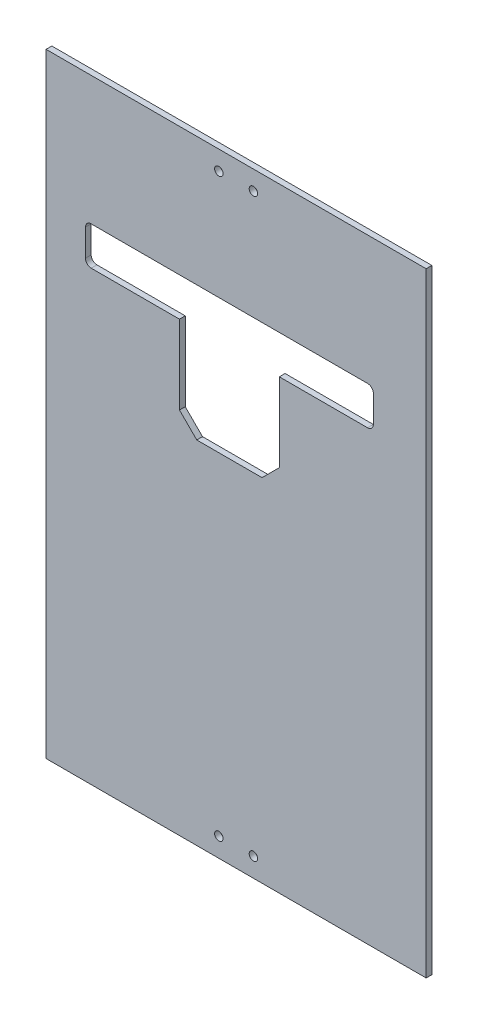
SolidWorks part; units mm, degrees
ref_plane "Plan de face" through (0, 0, 0) normal (0, 0, 1) x (1, 0, 0)
ref_plane "Plan de dessus" through (0, 0, 0) normal (0, 1, 0) x (1, 0, 0)
ref_plane "Plan de droite" through (0, 0, 0) normal (1, 0, 0) x (0, 0, -1)
sketch "Esquisse1" plane through (0, 0, 0) normal (0, 0, 1) x (1, 0, 0)
  line L0 (0, 0) -> (99, 0) construction
  line L1 (0, 0) -> (-99, 0) construction
  line L2 (-99, 0) -> (-99, 165) construction
  line L3 (-99, 165) -> (99, 165)
  line L4 (99, 165) -> (99, -155)
  line L5 (99, -155) -> (-99, -155)
  line L7 (-99, 165) -> (-99, -155)
  dimension "D1" = 165
  dimension "D2" = 99
  dimension "D4" = 320
  dimension "D5" = 320
extrude "Boss.-Extru.1" add sketch "Esquisse1" along normal blind 3
sketch "Esquisse2" plane through (0, 0, 3) normal (0, 0, 1) x (1, 0, 0)
  line L0 (0, -155) -> (0, -145) construction
  line L1 (-99, -155) -> (99, -155) construction
  line L2 (0, -145) -> (9, -145) construction
  line L3 (0, -145) -> (-9, -145) construction
  line L4 (0, 165) -> (0, 155) construction
  line L5 (99, 165) -> (-99, 165) construction
  line L6 (0, 155) -> (9, 155) construction
  line L7 (0, 155) -> (-9, 155) construction
  circle A0 centre (9, -145) radius 2.2
  circle A1 centre (-9, -145) radius 2.2
  circle A2 centre (-9, 155) radius 2.2
  circle A3 centre (9, 155) radius 2.2
  dimension "D1" = 10
  dimension "D2" = 18
  dimension "D3" = 9
  dimension "D4" = 10
  dimension "D5" = 9
  dimension "D6" = 9
extrude "Enlèv. mat.-Extru.1" cut sketch "Esquisse2" against normal up to next
sketch "Esquisse3" plane through (0, 0, 3) normal (0, 0, 1) x (1, 0, 0)
  line L0 (-99, 165) -> (-99, 89)
  line L1 (-99, 165) -> (-99, -155) construction
  line L2 (-99, 89) -> (99, 89)
  line L3 (99, -155) -> (99, 165) construction
  line L4 (99, 89) -> (99, 165)
  line L5 (99, 165) -> (-99, 165)
sketch "Esquisse5" plane through (0, 0, 3) normal (0, 0, 1) x (1, 0, 0)
  line L0 (0, 165) -> (0, 78) construction
  line L1 (99, 165) -> (-99, 165) construction
  line L2 (0, 78) -> (-58.5, 78) construction
  line L3 (-58.5, 78) -> (-78.5, 78)
  line L4 (-78.5, 78) -> (-78.5, 98)
  line L5 (-78.5, 98) -> (-58.5, 98)
  line L6 (-58.5, 98) -> (-58.5, 78)
  line L7 (0, 78) -> (-1.5, 78) construction
  line L8 (-1.5, 78) -> (-21.5, 78)
  line L9 (-21.5, 78) -> (-21.5, 98)
  line L10 (-21.5, 98) -> (-1.5, 98)
  line L11 (-1.5, 98) -> (-1.5, 78)
  line L12 (0, 78) -> (55.5, 78) construction
  line L13 (55.5, 78) -> (55.5, 98)
  line L14 (55.5, 98) -> (35.5, 98)
  line L15 (35.5, 98) -> (35.5, 78)
  line L16 (35.5, 78) -> (55.5, 78)
  line L17 (-58.5, 98) -> (-21.5, 98) construction
  line L18 (-1.5, 98) -> (35.5, 98) construction
  line L19 (-68.5, 78) -> (-68.5, 98) construction
  line L20 (-11.5, 78) -> (-11.5, 98) construction
  line L21 (45.5, 78) -> (45.5, 98) construction
  line L22 (-11.5, 78) -> (-5.5, 78) construction
  line L23 (-5.5, 78) -> (0, 78) construction
  line L24 (-68.5, 78) -> (-62.5, 78) construction
  line L25 (-62.5, 78) -> (0, 78) construction
  line L26 (45.5, 78) -> (51.5, 78) construction
  dimension "D1" = 87
  dimension "D2" = 58.5
  dimension "D3" = 1.5
  dimension "D4" = 20
  dimension "D5" = 20
  dimension "D6" = 20
  dimension "D7" = 37
  dimension "D8" = 37
  dimension "D9" = 20
  dimension "D10" = 55.5
  dimension "D11" = 5.5
  dimension "D12" = 6
  dimension "D13" = 20
  dimension "D14" = 51.5
extrude "Enlèv. mat.-Extru.4" cut sketch "Esquisse5" against normal up to next
sketch "Esquisse7" plane through (0, 0, 3) normal (0, 0, 1) x (1, 0, 0)
  line L0 (-68.5, 98) -> (71.5, 98)
  line L1 (-58.5, 98) -> (-78.5, 98) construction
  line L2 (-68.5, 78) -> (71.5, 78)
  line L3 (-78.5, 78) -> (-58.5, 78) construction
  line L4 (71.5, 78) -> (71.5, 98)
  dimension "D1" = 140
extrude "Enlèv. mat.-Extru.5" cut sketch "Esquisse7" against normal through all and the other way through all
fillet "Congé2" radius 3 4 edges at (-78.5, 78, 1.5) (-78.5, 98, 1.5) (71.5, 98, 1.5) (71.5, 78, 1.5)
sketch "Esquisse9" plane through (0, 0, 3) normal (0, 0, 1) x (1, 0, 0)
  line L0 (-3.5, 78) -> (-3.5, 28) construction
  line L1 (-75.5, 78) -> (68.5, 78) construction
  line L2 (-3.5, 28) -> (13.5, 28)
  line L3 (-3.5, 28) -> (-20.5, 28)
  line L4 (-20.5, 28) -> (-20.5, 37) construction
  line L5 (-20.5, 37) -> (-29.5, 37) construction
  line L6 (-20.5, 28) -> (-29.5, 37)
  line L7 (13.5, 28) -> (13.5, 37) construction
  line L8 (13.5, 37) -> (22.5, 37) construction
  line L9 (22.5, 37) -> (13.5, 28)
  line L10 (-29.5, 37) -> (-29.5, 78)
  line L11 (22.5, 37) -> (22.5, 78)
  line L12 (22.5, 78) -> (-29.5, 78)
  line L13 (-3.5, 28) -> (-3.5, 73) construction
  dimension "D1" = 50
  dimension "D2" = 17
  dimension "D3" = 17
extrude "Enlèv. mat.-Extru.6" cut sketch "Esquisse9" against normal up to next
